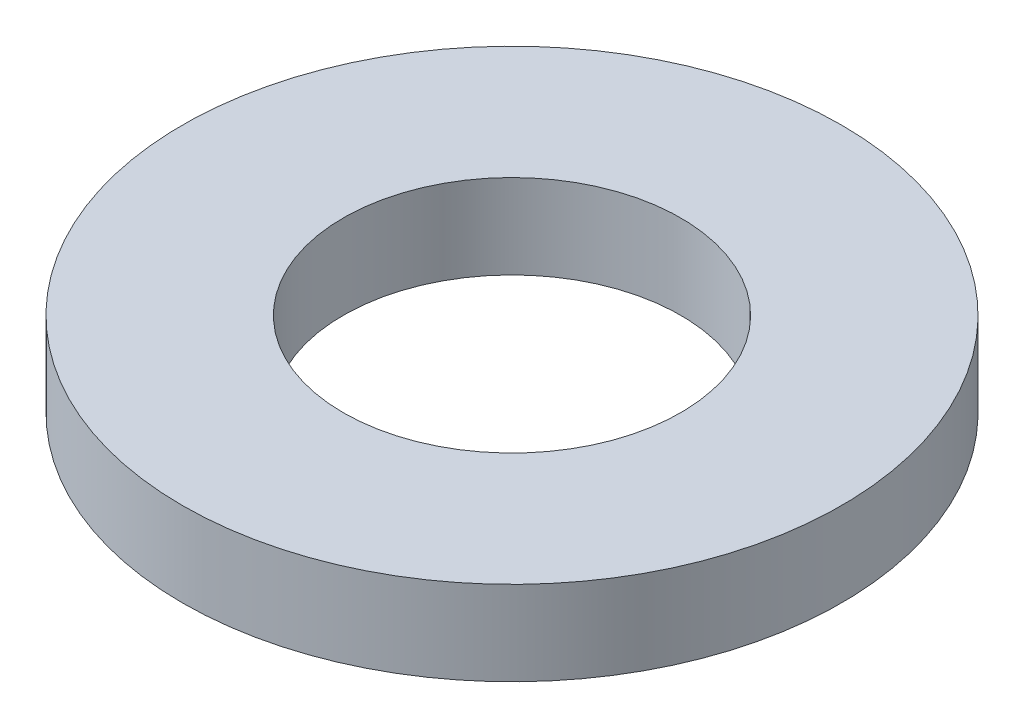
SolidWorks part; units mm, degrees
ref_plane "Front Plane" through (0, 0, 0) normal (0, 0, 1) x (1, 0, 0)
ref_plane "Top Plane" through (0, 0, 0) normal (0, 1, 0) x (1, 0, 0)
ref_plane "Right Plane" through (0, 0, 0) normal (1, 0, 0) x (0, 0, -1)
sketch "Эскиз1" plane through (0, 0, 0) normal (0, 1, 0) x (1, 0, 0)
  circle A0 centre (0, 0) radius 6.25
  circle A1 centre (0, 0) radius 3.2
  dimension "D1" = 6.4
  dimension "D2" = 12.5
extrude "Вытянуть1" add sketch "Эскиз1" along normal blind 1.6
